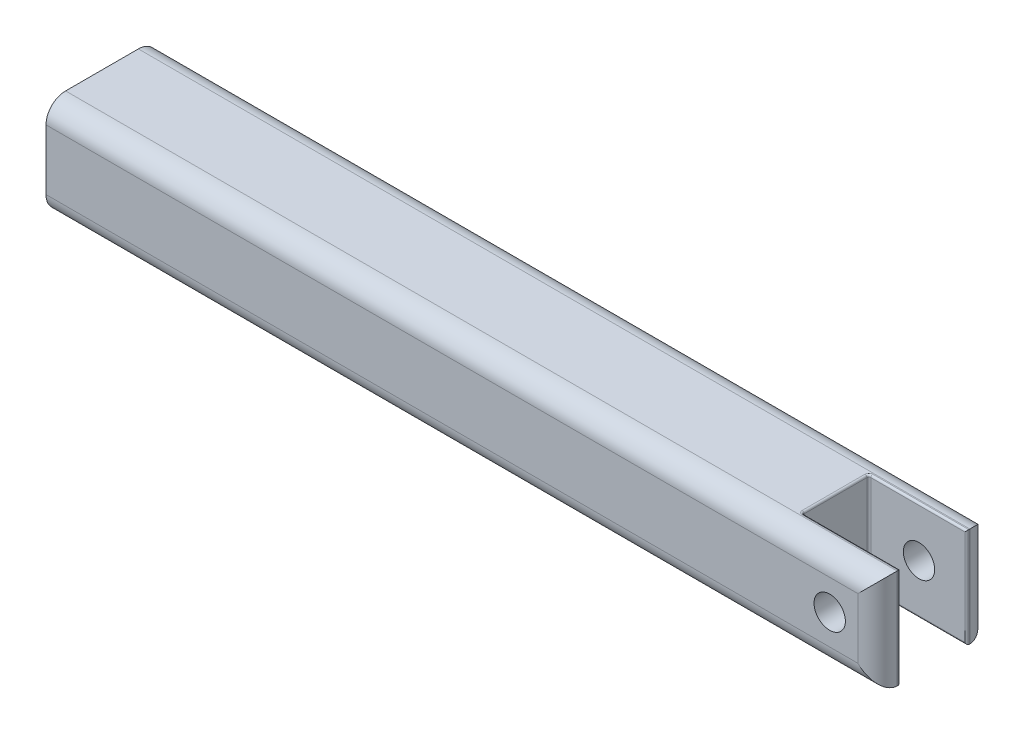
SolidWorks part; units mm, degrees
material "Chrome Stainless Steel"
ref_plane "Front Plane" through (0, 0, 0) normal (0, 0, 1) x (1, 0, 0)
ref_plane "Top Plane" through (0, 0, 0) normal (0, 1, 0) x (1, 0, 0)
ref_plane "Right Plane" through (0, 0, 0) normal (1, 0, 0) x (0, 0, -1)
sketch "Sketch1" plane through (0, 0, 0) normal (0, 0, 1) x (1, 0, 0)
  line L0 (-461.7, 0) -> (-106.1, 0) construction
  line L5 (106.1, -12.7) -> (-106.1, -12.7)
  line L6 (106.1, -12.7) -> (106.1, 12.7)
  line L7 (106.1, 12.7) -> (-106.1, 12.7)
  line L8 (-106.1, -12.7) -> (-106.1, 12.7)
  point P0 (0, 0)
  point P6 (0, 12.7)
  point P8 (0, -12.7)
  point P10 (-106.1, 0)
  point P11 (106.1, 0)
  dimension "r_end_length" = 212.2
  dimension "D2" = 25.4
extrude "Boss-Extrude1" add sketch "Sketch1" along normal mid plane 28.575
sketch "Sketch2" plane through (0, 0, 0) normal (0, 0, 1) x (1, 0, 0)
  line L0 (0, 30.5491) -> (0, -26.6873) construction
  line L1 (106.1, -12.7) -> (106.1, 12.7) construction
  circle A0 centre (93.9, 0) radius 4
  dimension "D1" = 12.2
  dimension "D2" = 8
extrude "Cut-Extrude2" cut sketch "Sketch2" against normal through all both and the other way through all
sketch "Sketch3" plane through (0, 0, 0) normal (0, 1, 0) x (1, 0, 0)
  line L0 (106.1, 8.5) -> (81.1, 8.5)
  line L1 (106.1, -14.2875) -> (106.1, 14.2875) construction
  line L2 (81.1, 8.5) -> (81.1, -8.5)
  line L3 (81.1, -8.5) -> (106.1, -8.5)
  line L4 (106.1, -8.5) -> (106.1, 8.5)
  point P6 (81.1, 0)
  point P7 (106.1, 0)
  dimension "D1" = 25
  dimension "D2" = 17
extrude "Cut-Extrude3" cut sketch "Sketch3" against normal through all both and the other way through all
fillet "Fillet3" radius 5 6 edges at (106.1, 0, -14.2875) (106.1, 0, 14.2875) (0, -12.7, 14.2875) (0, -12.7, -14.2875) (0, 12.7, -14.2875) (0, 12.7, 14.2875)
fillet "Fillet4" radius 0.5 10 edges at (81.1, -12.7, 0) (81.1, 12.7, 0) (93.6, -12.7, -8.5) (106.1, 0, 8.5) (93.6, -12.7, 8.5) (93.6, 12.7, 8.5) (81.1, 0, 8.5) (93.6, 12.7, -8.5) (81.1, 0, -8.5) (106.1, 0, -8.5)
ref_plane "Plane1" through (-106.1, 0, 0) normal (-1, 0, 0) x (0, 0, 1)
sketch "Sketch4" plane through (-106.1, 0, 0) normal (-1, 0, 0) x (0, 0, 1)
  point P0 (0, 0)
sketch "Sketch5" plane through (0, 0, 0) normal (0, 1, 0) x (1, 0, 0)
  line L0 (0, 0) -> (93.9, 0) construction
sketch3d "3DSketch1"
  point P0 (93.9, 0, 0)
equation "\"rack_length\"= 200mm"
equation "\"rack_end_length\"= - 0.5 * \"rack_length\" + 312.2mm"
equation "\"r_end_length@Sketch1\"=\"rack_end_length\""
